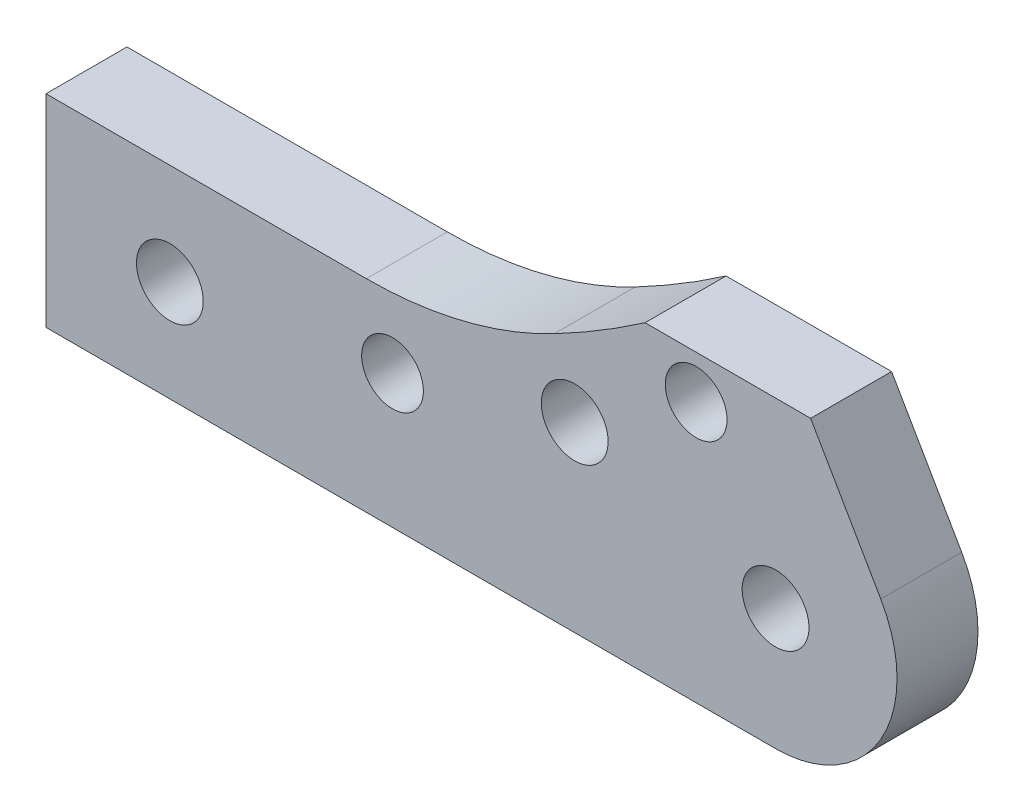
SolidWorks part; units mm, degrees
material "6061 合金"
ref_plane "前视基准面" through (0, 0, 0) normal (0, 0, 1) x (1, 0, 0)
ref_plane "上视基准面" through (0, 0, 0) normal (0, 1, 0) x (1, 0, 0)
ref_plane "右视基准面" through (0, 0, 0) normal (1, 0, 0) x (0, 0, -1)
other "Configuration Table"
sketch "草图1" plane through (0, 0, 0) normal (0, 0, 1) x (1, 0, 0)
  line L0 (13.1694, 42.8989) -> (45.1694, 42.8989)
  line L1 (45.1694, 42.8989) -> (54.407, 26.8989)
  line L3 (49.2109, 17.8989) -> (25.1694, 17.8989)
  line L4 (25.1694, 17.8989) -> (13.1694, 17.8989)
  line L5 (13.1694, 17.8989) -> (13.1694, 42.8989)
  arc A0 (54.407, 26.8989) -> (49.2109, 17.8989) centre (49.2109, 23.8989) cw
  circle A1 centre (49.2109, 23.8989) radius 1.65
  dimension "D4" = 3.3
  dimension "D6" = 6
  dimension "D1" = 24.0415
  dimension "D2" = 12
  dimension "D3" = 25
  dimension "D7" = 60
extrude "凸台-拉伸1" add sketch "草图1" along normal blind 4
sketch "草图2" plane through (0, 0, 4) normal (0, 0, 1) x (1, 0, 0)
  line L0 (13.1694, 32.8989) -> (50.9429, 32.8989)
  line L1 (13.1694, 42.8989) -> (13.1694, 17.8989) construction
  line L2 (54.407, 26.8989) -> (45.1694, 42.8989) construction
  line L3 (45.1694, 42.8989) -> (13.1694, 42.8989) construction
  line L4 (13.1694, 32.8989) -> (13.1694, 44.8647)
  line L5 (13.1694, 44.8647) -> (50.9429, 44.8647)
  line L6 (50.9429, 44.8647) -> (50.9429, 32.8989)
  dimension "D1" = 10
extrude "切除-拉伸1" cut sketch "草图2" against normal blind 10
sketch "草图4" plane through (0, 0, 4) normal (0, 0, 1) x (1, 0, 0)
  circle A0 centre (19.2874, 22.8989) radius 1.65
  circle A1 centre (39.2874, 26.8989) radius 1.65
extrude "切除-拉伸3" cut sketch "草图4" against normal blind 10
sketch "草图3" plane through (0, 0, 0) normal (0, 0, -1) x (-1, 0, 0)
  line L0 (-13.1694, 27.8989) -> (-33.1181, 27.8989)
  line L1 (-13.1694, 32.8989) -> (-13.1694, 17.8989) construction
  line L2 (-13.1694, 17.8989) -> (-49.2109, 17.8989) construction
  line L3 (-13.1694, 27.8989) -> (-13.1694, 32.8989)
  line L4 (-13.1694, 32.8989) -> (-42.7644, 32.8989)
  arc A2 (-42.7644, 32.8989) -> (-33.1181, 27.8989) centre (-18.3739, 68.1497) ccw
  dimension "D1" = 10
extrude "切除-拉伸2" cut sketch "草图3" against normal blind 10
fillet "圆角1" radius 20 1 edges at (33.1181, 27.8989, 2)
sketch "草图5" plane through (0, 0, 4) normal (0, 0, 1) x (1, 0, 0)
  circle A0 centre (30.2874, 24.4996) radius 1.525
  circle A1 centre (45.2874, 30.7648) radius 1.525
extrude "切除-拉伸4" cut sketch "草图5" against normal blind 12
